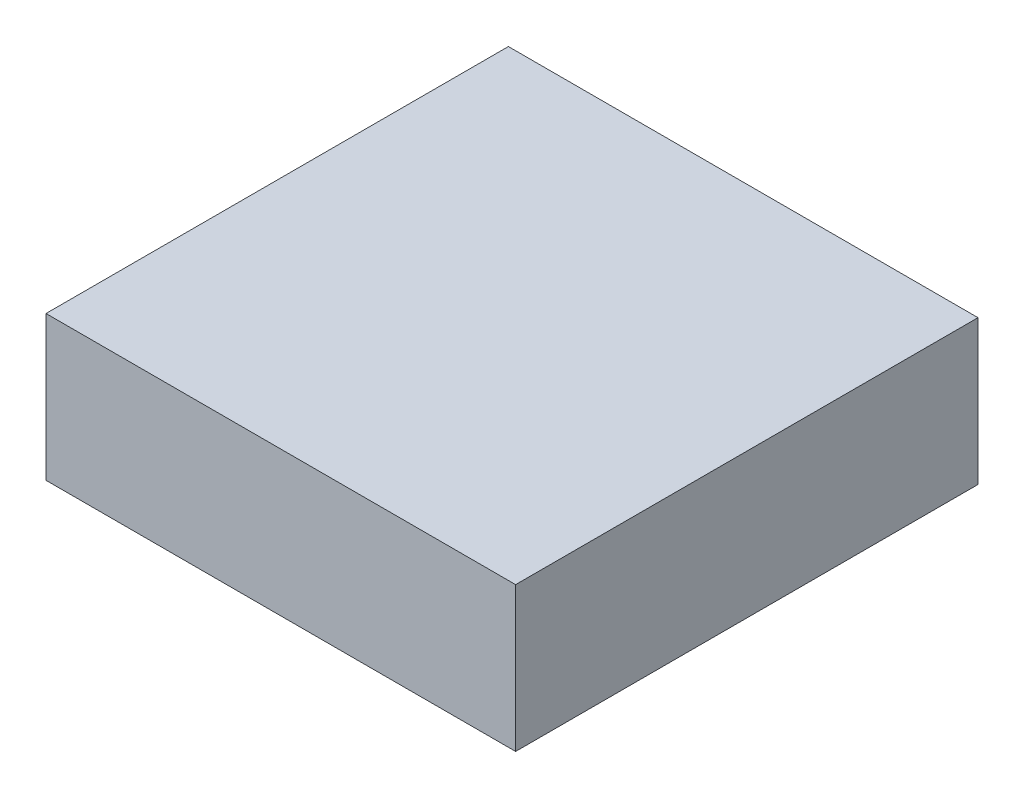
SolidWorks part; units mm, degrees
material "Özel Plastik"
ref_plane "Ön Düzlem" through (0, 0, 0) normal (0, 0, 1) x (1, 0, 0)
ref_plane "Üst Düzlem" through (0, 0, 0) normal (0, 1, 0) x (1, 0, 0)
ref_plane "Sağ Düzlem" through (0, 0, 0) normal (1, 0, 0) x (0, 0, -1)
sketch "Çizim1" plane through (0, 0, 0) normal (0, 1, 0) x (1, 0, 0)
  line L1 (-32.5, -32) -> (32.5, -32)
  line L2 (-32.5, -32) -> (-32.5, 32)
  line L3 (-32.5, 32) -> (32.5, 32)
  line L4 (32.5, -32) -> (32.5, 32)
  line L5 (0, 32) -> (0, -32) construction
  line L6 (-32.5, 0) -> (32.5, 0) construction
  point P0 (0, 0)
  dimension "D1" = 65
  dimension "D2" = 64
extrude "Yükseklik-Ekstrüzyon1" add sketch "Çizim1" along normal blind 20
